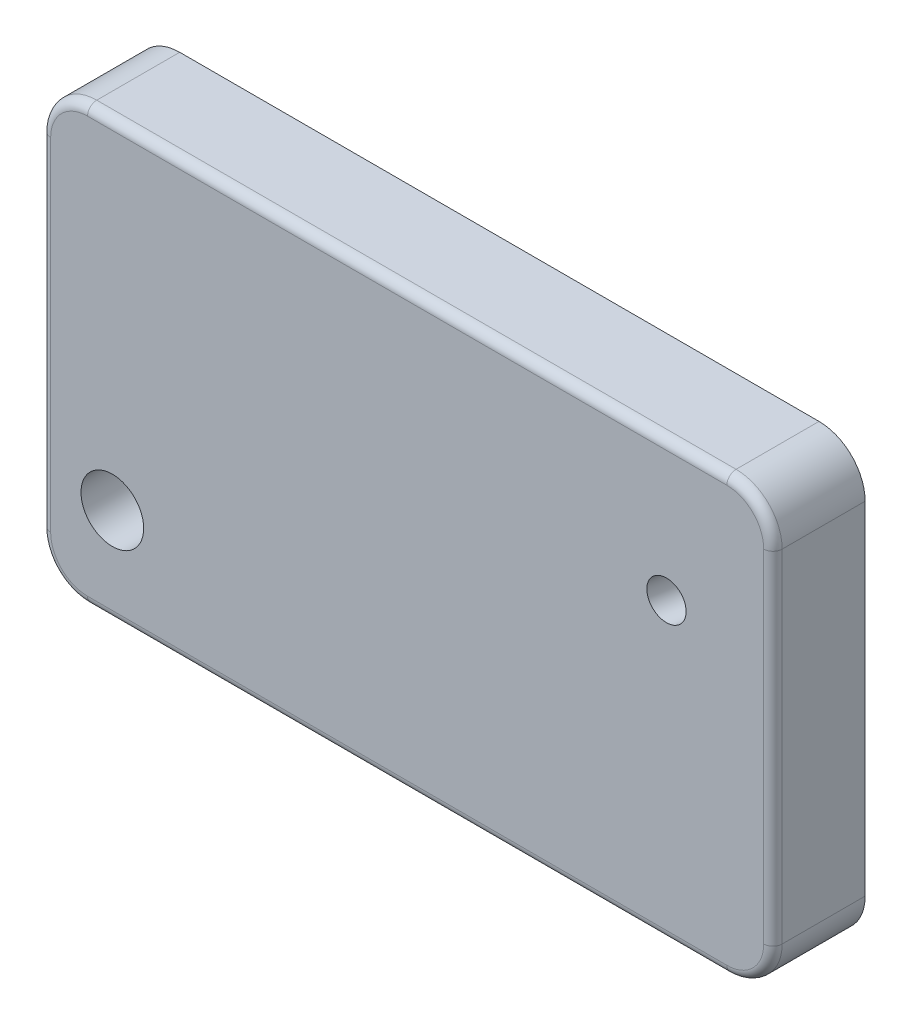
SolidWorks part; units mm, degrees
ref_plane "前视基准面" through (0, 0, 0) normal (0, 0, 1) x (1, 0, 0)
ref_plane "上视基准面" through (0, 0, 0) normal (0, 1, 0) x (1, 0, 0)
ref_plane "右视基准面" through (0, 0, 0) normal (1, 0, 0) x (0, 0, -1)
sketch "Sketch1" plane through (0, 0, 0) normal (0, 0, 1) x (1, 0, 0)
  line L1 (-49.3825, 22.0797) -> (42.9799, 22.0797)
  line L2 (-49.3825, 22.0797) -> (-49.3825, -7.9203)
  line L3 (-49.3825, -7.9203) -> (42.9799, -7.9203)
  line L4 (42.9799, 22.0797) -> (42.9799, -7.9203)
  line L5 (-49.3825, -7.9203) -> (-5.6825, -7.9203)
  line L6 (-49.3825, -7.9203) -> (-49.3825, -41.0233)
  line L7 (-49.3825, -41.0233) -> (-5.6825, -41.0233)
  line L8 (-5.6825, -7.9203) -> (-5.6825, -41.0233)
  line L9 (-5.6825, -7.9203) -> (42.9799, -7.9203)
  line L10 (-5.6825, -7.9203) -> (-5.6825, -41.0233)
  line L11 (-5.6825, -41.0233) -> (42.9799, -41.0233)
  line L12 (42.9799, -7.9203) -> (42.9799, -41.0233)
  circle A0 centre (-31.8099, 6.9927) radius 2.5
  circle A1 centre (33.1901, 6.9927) radius 1
  dimension "D4" = 9.7898
  dimension "D1" = 15.087
  dimension "D2" = 30
  dimension "D3" = 65
extrude "Boss-Extrude1" add sketch "Sketch1" along normal blind 10 contours L1 L4 L3 L2 | L6 L5 L8 L7
sketch "Sketch4" plane through (0, 0, 0) normal (0, 0, -1) x (-1, 0, 0)
  circle A1 centre (31.8099, 6.9927) radius 2.5
ref_plane "Plane1" through (0, 7.0797, 0) normal (0, -1, 0) x (-1, 0, 0)
sketch "Sketch10" plane through (0, 7.0797, 0) normal (0, -1, 0) x (-1, 0, 0)
  line L0 (-41.6731, 0) -> (-24.7071, 0)
  line L1 (49.3825, 0) -> (-42.9799, 0) construction
  line L2 (-24.7071, 0) -> (-24.7071, 2.9916)
  line L3 (-24.7071, 2.9916) -> (-41.6731, 0)
  dimension "D1" = 10
  dimension "D2" = 8.483
  dimension "D3" = 8.483
extrude "Boss-Extrude2" add sketch "Sketch10" along normal mid plane 20
sketch "Sketch11" plane through (1.2566, 0, -7.1265) normal (0.1736, 0, -0.9848) x (-0.9848, 0, -0.1736)
  circle A0 centre (-32.6859, 6.9927) radius 1
hole_wizard "M3 Tapped Hole1" positions "3DSketch9" profile "Sketch12" tap size "M5" standard "GB" end condition through all
sketch3d "3DSketch9"
  point P0 (33.4459, 6.9927, -1.4507)
sketch "Sketch12" plane through (33.4459, 6.9927, -1.4507) normal (0, 1, 0) x (-0.9848, 0, -0.1736)
  line L0 (0, 0) -> (0, 25.6597)
  line L1 (0, 25.6597) -> (2.1, 25.6597)
  line L2 (2.1, 25.6597) -> (2.1, 0)
  line L5 (2.1, 0) -> (0, 0)
  line L11 (0, -6.35) -> (0, 107.95) construction
  dimension "Thru Tap Drill Dia." = 4.2
  dimension "Thru Tap Drill Depth" = 25.6597
cosmetic thread "Hole Thread1" parameters "D2"=5
sketch "Sketch13" plane through (0, 0, 10) normal (0, 0, 1) x (1, 0, 0)
  line L0 (-49.3825, 22.0797) -> (-49.3825, -41.0233) construction
  line L2 (-49.3825, -41.0233) -> (-5.6825, -41.0233) construction
  circle A0 centre (-28.6925, -14.5433) radius 2.5
  dimension "D3" = 5
  dimension "D1" = 20.69
  dimension "D2" = 26.48
sketch "Sketch15" plane through (0, 0, 0) normal (0, 0, -1) x (-1, 0, 0)
  line L0 (49.3825, 22.0797) -> (49.3825, -41.0233) construction
  line L1 (5.6825, -41.0233) -> (49.3825, -41.0233)
  line L2 (5.6825, -41.0233) -> (5.6825, -25.0233)
  line L3 (5.6825, -25.0233) -> (49.3825, -25.0233)
  line L4 (49.3825, -41.0233) -> (49.3825, -25.0233)
  line L5 (49.3825, 22.0797) -> (-42.9799, 22.0797) construction
  line L6 (49.3825, -25.0233) -> (36.3825, -25.0233)
  line L7 (49.3825, -25.0233) -> (49.3825, 22.0797)
  line L8 (49.3825, 22.0797) -> (36.3825, 22.0797)
  line L9 (36.3825, -25.0233) -> (36.3825, 22.0797)
  line L11 (5.6825, -7.9203) -> (15.6825, -7.9203)
  line L12 (5.6825, -7.9203) -> (5.6825, -25.0233)
  line L13 (5.6825, -25.0233) -> (15.6825, -25.0233)
  line L14 (15.6825, -7.9203) -> (15.6825, -25.0233)
  line M11 (49.3825, -41.0233) -> (49.3825, 22.0797)
  line M12 (49.3825, 22.0797) -> (-42.9799, 22.0797)
  line M15 (5.6825, -7.9203) -> (5.6825, -41.0233)
  line M16 (5.6825, -41.0233) -> (49.3825, -41.0233)
extrude "Cut-Extrude1" cut sketch "Sketch15" against normal blind 10 contours L3 M15 M16 M11 | L14 L11 L3 M15 | L9 L3 M11 M12
sketch "Sketch18" plane through (0, 0, 0) normal (0, 0, -1) x (-1, 0, 0)
  line L0 (-42.9799, 22.0797) -> (-42.9799, -7.9203) construction
  line L1 (15.6825, -7.9203) -> (-42.9799, -7.9203)
  line L2 (15.6825, -7.9203) -> (15.6825, -25.0233)
  line L3 (15.6825, -25.0233) -> (-42.9799, -25.0233)
  line L4 (-42.9799, -7.9203) -> (-42.9799, -25.0233)
  line L5 (15.6825, -25.0233) -> (36.3825, -25.0233) construction
extrude "Boss-Extrude4" add sketch "Sketch18" against normal blind 10
sketch "Sketch19" plane through (0, 0, 0) normal (0, 0, -1) x (-1, 0, 0)
  line L1 (36.3825, -25.0233) -> (15.7305, -25.0233)
  line L2 (36.3825, -25.0233) -> (36.3825, -4.3713)
  line L3 (31.3825, 0.6287) -> (15.7305, 0.6287)
  line L4 (10.7305, -20.0233) -> (10.7305, -4.3713)
  arc A0 (36.3825, -4.3713) -> (31.3825, 0.6287) centre (31.3825, -4.3713) ccw
  arc A1 (15.7305, -25.0233) -> (10.7305, -20.0233) centre (15.7305, -20.0233) cw
  arc A2 (15.7305, 0.6287) -> (10.7305, -4.3713) centre (15.7305, -4.3713) ccw
  dimension "D1" = 5
extrude "Boss-Extrude5" add sketch "Sketch19" along normal blind 20
sketch "Sketch22" plane through (0, 0, 10) normal (0, 0, 1) x (1, 0, 0)
  line L0 (-36.3825, 22.0797) -> (42.9799, 22.0797) construction
  line L1 (-36.3825, -25.0233) -> (-36.3825, 22.0797) construction
  circle A0 centre (-28.6925, -14.6103) radius 3.9776
  dimension "D1" = 36.69
  dimension "D2" = 7.69
hole_wizard "M8 Tapped Hole2" positions "3DSketch10" profile "Sketch23" tap size "M8" standard "GB" end condition through all
sketch3d "3DSketch10"
  point P0 (-28.6925, -14.6103, 10)
sketch "Sketch23" plane through (-28.6925, -14.6103, 10) normal (1, 0, 0) x (0, -1, 0)
  line L0 (0, 0) -> (0, 30)
  line L1 (0, 30) -> (3.4, 30)
  line L2 (3.4, 30) -> (3.4, 0)
  line L5 (3.4, 0) -> (0, 0)
  line L11 (0, -6.35) -> (0, 107.95) construction
  dimension "Thru Tap Drill Dia." = 6.8
  dimension "Thru Tap Drill Depth" = 30
cosmetic thread "Hole Thread2" parameters "D2"=8
fillet "Fillet1" radius 5 4 edges at (-36.3825, 22.0797, 5) (42.9799, 22.0797, 5) (42.9799, -25.0233, 5) (-36.3825, -25.0233, -5)
fillet "Fillet2" radius 1 8 edges at (-34.918, 20.6152, 10) (-36.3825, -1.4718, 10) (-34.918, -23.5588, 10) (3.2987, -25.0233, 10) (41.5154, -23.5588, 10) (42.9799, -1.4718, 10) (41.5154, 20.6152, 10) (3.2987, 22.0797, 10)
